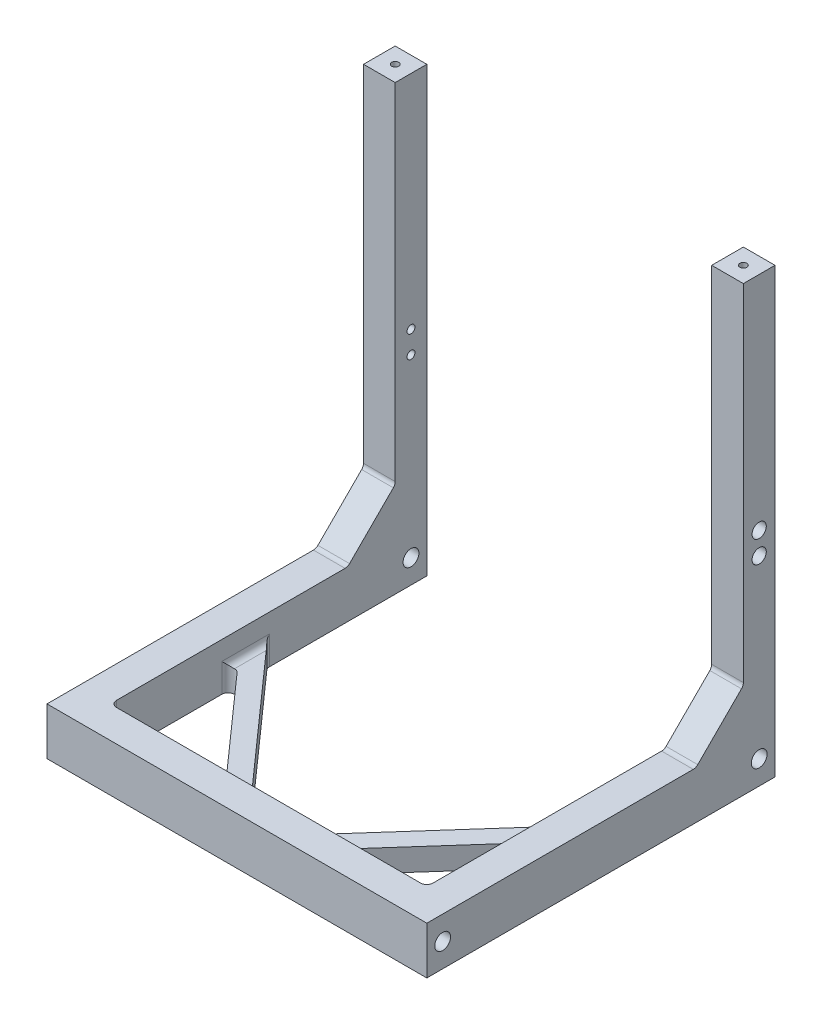
SolidWorks part; units mm, degrees
material "PLA"
ref_plane "Front Plane" through (0, 0, 0) normal (0, 0, 1) x (1, 0, 0)
ref_plane "Top Plane" through (0, 0, 0) normal (0, 1, 0) x (1, 0, 0)
ref_plane "Right Plane" through (0, 0, 0) normal (1, 0, 0) x (0, 0, -1)
sketch "Sketch1" plane through (0, 0, 0) normal (0, 1, 0) x (1, 0, 0)
  line L0 (-76.2, 139.7) -> (-76.2, 0)
  line L1 (-76.2, 0) -> (76.2, 0)
  line L3 (63.5, 12.7) -> (-63.5, 12.7)
  line L4 (-63.5, 12.7) -> (-63.5, 139.7)
  line L5 (-63.5, 139.7) -> (-76.2, 139.7)
  line L6 (0, 4.6965) -> (0, 50004.6965) construction
  line L7 (63.5, 139.7) -> (76.2, 139.7)
  line L8 (63.5, 12.7) -> (63.5, 139.7)
  line L9 (76.2, 139.7) -> (76.2, 0)
  point P12 (0, 12.7)
  point P13 (0, 0)
  dimension "D1" = 12.7
  dimension "D2" = 12.7
  dimension "D3" = 127
  dimension "D4" = 127
extrude "Boss-Extrude1" add sketch "Sketch1" along normal blind 19.05
sketch "Sketch2" plane through (0, 0, -139.7) normal (0, 0, -1) x (-1, 0, 0)
  line L0 (-76.2, 19.05) -> (-76.2, 177.8)
  line L1 (-76.2, 177.8) -> (-63.5, 177.8)
  line L2 (-63.5, 177.8) -> (-63.5, 19.05)
  line L3 (-63.5, 19.05) -> (-76.2, 19.05)
  line L4 (0, 0) -> (0, 50000) construction
  line L6 (-76.2, 0) -> (-63.5, 0) construction
  line L7 (63.5, 19.05) -> (76.2, 19.05)
  line L8 (63.5, 177.8) -> (63.5, 19.05)
  line L9 (76.2, 177.8) -> (63.5, 177.8)
  line L10 (76.2, 19.05) -> (76.2, 177.8)
  dimension "D1" = 177.8
extrude "Boss-Extrude2" add sketch "Sketch2" against normal blind 12.7 separate body
sketch "Sketch3" plane through (76.2, 0, 0) normal (1, 0, 0) x (0, 0, -1)
  line L0 (127, 38.1) -> (107.95, 19.05)
  line L1 (127, 177.8) -> (127, 19.05) construction
  line L2 (0, 19.05) -> (139.7, 19.05) construction
  line L3 (107.95, 19.05) -> (127, 19.05)
  line L4 (127, 19.05) -> (127, 38.1)
  dimension "D1" = 19.05
  dimension "D2" = 19.05
extrude "Boss-Extrude3" add sketch "Sketch3" against normal up to surface (12.7 mm away) up to face at (63.5, 98.425, -133.35)
sketch "Sketch4" plane through (-76.2, 0, 0) normal (-1, 0, 0) x (0, 0, 1)
  line L0 (-127, 38.1) -> (-107.95, 19.05) construction
  line L1 (-127, 38.1) -> (-107.95, 19.05)
  line L2 (-127, 38.1) -> (-127, 19.05)
  line L3 (-139.7, 19.05) -> (0, 19.05) construction
  line L4 (-127, 19.05) -> (-107.95, 19.05)
extrude "Boss-Extrude4" add sketch "Sketch4" against normal up to surface (12.7 mm away) up to face at (-63.5, 98.425, -133.35)
sketch "Sketch5" plane through (76.2, 0, 0) normal (1, 0, 0) x (0, 0, -1)
  line L0 (133.35, 177.8) -> (133.35, 0) construction
  line L1 (127, 177.8) -> (139.7, 177.8) construction
  line L2 (0, 0) -> (139.7, 0) construction
  circle A0 centre (133.35, 88.9) radius 1.5875
  circle A1 centre (133.35, 80.01) radius 1.5875
  dimension "D1" = 3.175
  dimension "D3" = 3.175
  dimension "D2" = 88.9
  dimension "D4" = 8.89
extrude "Cut-Extrude1" cut sketch "Sketch5" against normal through all
sketch "Sketch6" plane through (76.2, 0, 0) normal (1, 0, 0) x (0, 0, -1)
  line L0 (133.35, 88.9) -> (133.35, 80.01) construction
  line L1 (133.35, 84.455) -> (139.7, 84.455) construction
  line L2 (139.7, 177.8) -> (139.7, 0) construction
  circle A0 centre (133.35, 88.9) radius 2.8575
  circle A1 centre (133.35, 80.01) radius 2.8575
  dimension "D1" = 5.715
extrude "Cut-Extrude2" cut sketch "Sketch6" against normal blind 5.08
mirror "Mirror2" about plane through (0, 0, 0) normal (1, 0, 0) of "Cut-Extrude2"
sketch "Sketch7" plane through (0, 0, 0) normal (0, -1, 0) x (1, 0, 0)
  line L0 (-17.7976, -12.7) -> (-63.5, -64.1152)
  line L1 (63.5, -12.7) -> (-63.5, -12.7) construction
  line L2 (-63.5, -12.7) -> (-63.5, -139.7) construction
  line L3 (-63.5, -64.1152) -> (-63.5, -75.5848)
  line L4 (-63.5, -75.5848) -> (-7.6024, -12.7)
  line L5 (-7.6024, -12.7) -> (-17.7976, -12.7)
  line L6 (0, 0) -> (0, -12.7) construction
  line L7 (-76.2, 0) -> (76.2, 0) construction
  line L8 (-76.2, -139.7) -> (-76.2, 0) construction
  line L9 (7.6024, -12.7) -> (17.7976, -12.7)
  line L10 (63.5, -75.5848) -> (7.6024, -12.7)
  line L11 (63.5, -64.1152) -> (63.5, -75.5848)
  line L12 (17.7976, -12.7) -> (63.5, -64.1152)
  point P11 (-63.5, -69.85)
  point P15 (-12.7, -12.7)
  dimension "D1" = 69.85
  dimension "D2" = 7.62
  dimension "D3" = 63.5
extrude "Boss-Extrude5" add sketch "Sketch7" against normal blind 8.89
sketch "Sketch8" plane through (0, 177.8, 0) normal (0, 1, 0) x (1, 0, 0)
  line L0 (69.85, 139.7) -> (69.85, 127) construction
  line L1 (63.5, 139.7) -> (76.2, 139.7) construction
  line L2 (63.5, 127) -> (76.2, 127) construction
  circle A0 centre (69.85, 133.35) radius 1.397
  dimension "D1" = 2.794
extrude "Cut-Extrude3" cut sketch "Sketch8" against normal blind 12.7
mirror "Mirror3" about plane through (0, 0, 0) normal (1, 0, 0) of "Cut-Extrude3"
fillet "Fillet1" radius 2.54 18 edges at (-63.5, 9.525, -12.7) (63.5, 9.525, -12.7) (63.5, 4.445, -64.1152) (63.5, 8.89, -69.85) (63.5, 4.445, -75.5848) (7.6024, 4.445, -12.7) (12.7, 8.89, -12.7) (17.7976, 4.445, -12.7) (-7.6024, 4.445, -12.7) (-12.7, 8.89, -12.7) (-17.7976, 4.445, -12.7) (-63.5, 4.445, -64.1152) (-63.5, 8.89, -69.85) (-63.5, 4.445, -75.5848) (69.85, 38.1, -127) (69.85, 19.05, -107.95) (-69.85, 38.1, -127) (-69.85, 19.05, -107.95)
sketch "Sketch9" plane through (76.2, 0, 0) normal (1, 0, 0) x (0, 0, -1)
  line L0 (12.7, 19.05) -> (12.7, 0) construction
  line L1 (12.7, 9.525) -> (0, 9.525) construction
  line L2 (0, 19.05) -> (0, 0) construction
  line L3 (139.7, 19.05) -> (127, 19.05) construction
  line L4 (139.7, 177.8) -> (139.7, 0) construction
  line L5 (127, 19.05) -> (127, 0) construction
  line L6 (0, 0) -> (139.7, 0) construction
  line L7 (127, 9.525) -> (139.7, 9.525) construction
  circle A0 centre (6.35, 9.525) radius 3.175
  circle A1 centre (133.35, 9.525) radius 3.175
  dimension "D1" = 6.35
  dimension "D3" = 6.35
  dimension "D2" = 12.7
extrude "Cut-Extrude4" cut sketch "Sketch9" against normal through all
